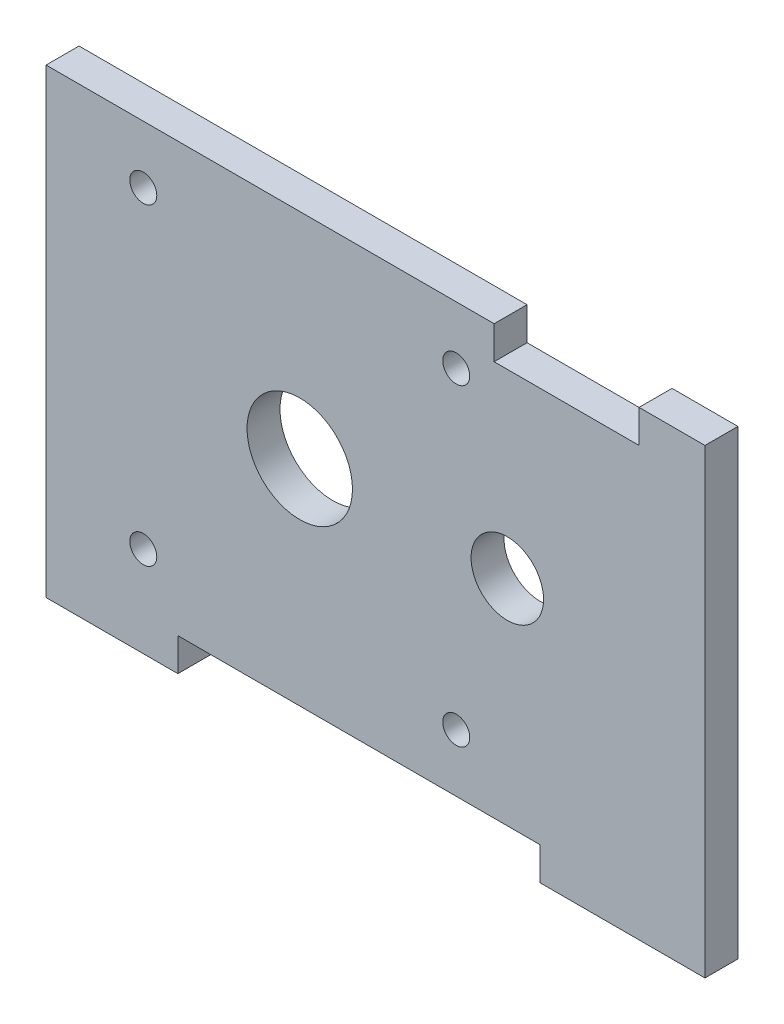
SolidWorks part; units mm, degrees
ref_plane "Front Plane" through (0, 0, 0) normal (0, 0, 1) x (1, 0, 0)
ref_plane "Top Plane" through (0, 0, 0) normal (0, 1, 0) x (1, 0, 0)
ref_plane "Right Plane" through (0, 0, 0) normal (1, 0, 0) x (0, 0, -1)
sketch "Sketch1" plane through (0, 0, 0) normal (0, 0, 1) x (1, 0, 0)
  line L0 (0, 0) -> (0, 82.55)
  line L1 (0, 82.55) -> (-127, 82.55)
  line L2 (-127, 82.55) -> (-127, 0)
  line L3 (-127, 0) -> (0, 0)
  line L4 (-127, 0) -> (-127, -6.35)
  line L5 (-127, -6.35) -> (-101.6, -6.35)
  line L6 (-101.6, -6.35) -> (-101.6, 0)
  line L7 (0, 0) -> (0, -6.35)
  line L8 (0, -6.35) -> (-31.75, -6.35)
  line L9 (-31.75, -6.35) -> (-31.75, 0)
  circle A0 centre (-38.1, 41.275) radius 6.985
  circle A1 centre (-78.105, 41.275) radius 10.16
  circle A2 centre (-78.105, 41.275) radius 30.48 construction
  circle A3 centre (-38.1, 41.275) radius 9.525 construction
  dimension "D1" = 20.32
  dimension "D2" = 13.97
  dimension "D6" = 60.96
  dimension "D7" = 19.05
  dimension "D3" = 38.1
  dimension "D4" = 40.005
  dimension "D5" = 41.275
  dimension "D8" = 82.55
  dimension "D9" = 127
  dimension "D10" = 6.35
  dimension "D11" = 31.75
  dimension "D12" = 6.35
  dimension "D13" = 25.4
extrude "Boss-Extrude1" add sketch "Sketch1" along normal blind 6.35 contours L2 L3 L0 L1 A1 A0 | L5 L6 L3 L4 | L9 L8 L7 L3
sketch "Sketch3" plane through (0, 0, 6.35) normal (0, 0, 1) x (1, 0, 0)
  line L0 (0, 82.55) -> (-127, 82.55) construction
  line L1 (-127, 82.55) -> (-127, -6.35) construction
  line L2 (-127, -6.35) -> (-101.6, -6.35) construction
  line L3 (-101.6, 0) -> (-31.75, 0) construction
  circle A0 centre (-108.2675, 71.4375) radius 2.6035
  circle A1 centre (-47.9425, 71.4375) radius 2.6035
  circle A2 centre (-108.2675, 11.1125) radius 2.6035
  circle A3 centre (-47.9425, 11.1125) radius 2.6035
  point P14 (0, 0)
  dimension "D1" = 5.207
  dimension "D6" = 5.207
  dimension "D9" = 5.207
  dimension "D10" = 5.207
  dimension "D2" = 11.1125
  dimension "D3" = 79.0575
  dimension "D4" = 11.1125
  dimension "D5" = 18.7325
  dimension "D7" = 18.7325
  dimension "D8" = 17.4625
  dimension "D11" = 79.0575
  dimension "D12" = 11.1125
extrude "Cut-Extrude1" cut sketch "Sketch3" against normal through all
sketch "Sketch4" plane through (0, 0, 0) normal (0, 0, -1) x (-1, 0, 0)
  line L0 (0, 82.55) -> (127, 82.55) construction
  line L1 (12.7, 82.55) -> (40.64, 82.55)
  line L2 (12.7, 82.55) -> (12.7, 76.2)
  line L3 (12.7, 76.2) -> (40.64, 76.2)
  line L4 (40.64, 82.55) -> (40.64, 76.2)
  line L5 (0, -6.35) -> (0, 82.55) construction
  dimension "D1" = 12.7
  dimension "D2" = 27.94
  dimension "D3" = 6.35
extrude "Cut-Extrude2" cut sketch "Sketch4" against normal blind 6.35
equation "\"D4@Sketch1\"=(.75+2.4)/2"
